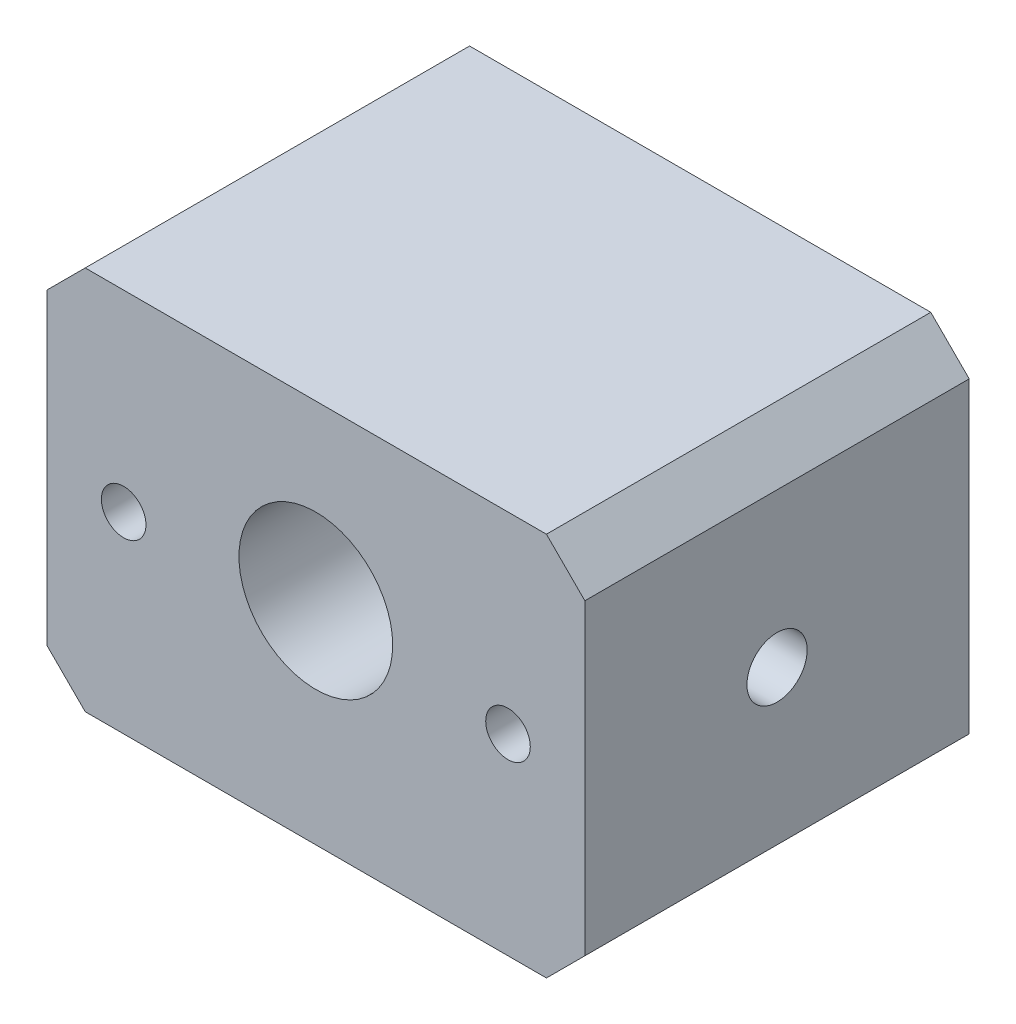
SolidWorks part; units mm, degrees
material "6063-T6"
ref_plane "Front Plane" through (0, 0, 0) normal (0, 0, 1) x (1, 0, 0)
ref_plane "Top Plane" through (0, 0, 0) normal (0, 1, 0) x (1, 0, 0)
ref_plane "Right Plane" through (0, 0, 0) normal (1, 0, 0) x (0, 0, -1)
sketch "Sketch1" plane through (0, 0, 0) normal (0, 0, 1) x (1, 0, 0)
  line L0 (-15.875, 0) -> (15.875, 0) construction
  line L1 (-22.225, -15.875) -> (22.225, -15.875)
  line L2 (-22.225, -15.875) -> (-22.225, 15.875)
  line L3 (-22.225, 15.875) -> (22.225, 15.875)
  line L4 (22.225, -15.875) -> (22.225, 15.875)
  line L5 (-22.225, -15.875) -> (22.225, 15.875) construction
  line L6 (-22.225, 15.875) -> (22.225, -15.875) construction
  circle A1 centre (-15.875, 0) radius 1.8415
  circle A2 centre (15.875, 0) radius 1.8415
  circle A3 centre (0, 1.5875) radius 6.35
  point P0 (0, 0)
  dimension "D4" = 12.7
  dimension "D5" = 3.683
  dimension "D6" = 6.35
  dimension "D7" = 6.35
  dimension "D1" = 31.75
  dimension "D2" = 44.45
  dimension "D3" = 15.875
  dimension "D8" = 1.5875
extrude "Boss-Extrude1" add sketch "Sketch1" along normal blind 31.75
chamfer "Chamfer1" distance 3.175 angle 45 4 edges at (-22.225, -15.875, 15.875) (-22.225, 15.875, 15.875) (22.225, -15.875, 15.875) (22.225, 15.875, 15.875)
sketch "Sketch2" plane through (22.225, 0, 0) normal (1, 0, 0) x (0, 0, -1)
  line L0 (67.2731, 0) -> (-67.2731, 0) construction
  line L1 (-31.75, -12.7) -> (-31.75, 12.7) construction
  circle A0 centre (-15.875, 0) radius 2.4892
  dimension "D1" = 4.9784
  dimension "D2" = 15.875
extrude "Cut-Extrude1" cut sketch "Sketch2" against normal through all
